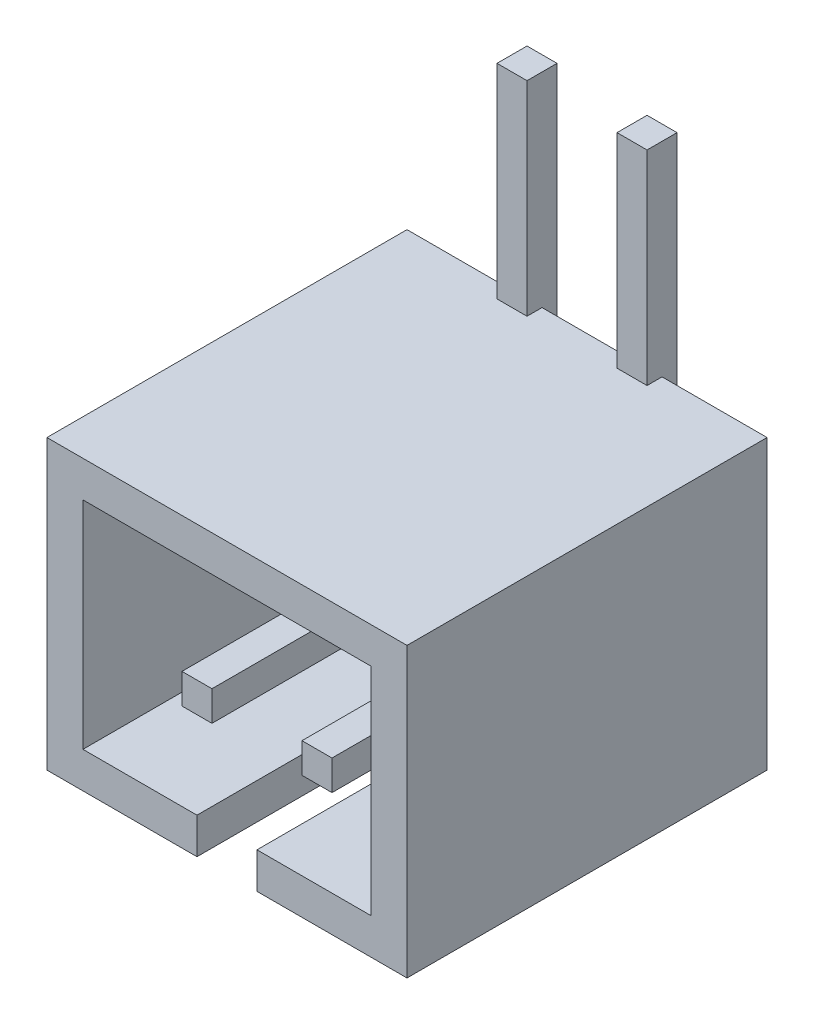
SolidWorks part; units mm, degrees
ref_plane "Front Plane" through (0, 0, 0) normal (0, 0, 1) x (1, 0, 0)
ref_plane "Top Plane" through (0, 0, 0) normal (0, 1, 0) x (1, 0, 0)
ref_plane "Right Plane" through (0, 0, 0) normal (1, 0, 0) x (0, 0, -1)
sketch "Sketch1" plane through (0, 0, 0) normal (0, 0, 1) x (1, 0, 0)
  line L1 (-3, 2.4) -> (3, 2.4)
  line L2 (-3, 2.4) -> (-3, -2.4)
  line L3 (-3, -2.4) -> (3, -2.4)
  line L4 (3, 2.4) -> (3, -2.4)
  line L5 (-3, 2.4) -> (3, -2.4) construction
  line L6 (-3, -2.4) -> (3, 2.4) construction
  point P0 (0, 0)
  dimension "D1" = 6
  dimension "D2" = 4.8
extrude "Boss-Extrude1" add sketch "Sketch1" along normal blind 2
sketch "Sketch2" plane through (0, 0, 2) normal (0, 0, 1) x (1, 0, 0)
  line L0 (-0.5, -2.4) -> (-0.5, -1.8)
  line L1 (-3, -2.4) -> (3, -2.4) construction
  line L2 (-0.5, -1.8) -> (-2.4, -1.8)
  line L3 (-2.4, -1.8) -> (-2.4, 1.8)
  line L4 (-2.4, 1.8) -> (2.4, 1.8)
  line L5 (0, 1.8) -> (0, 0) construction
  line L6 (-0.5, -2.4) -> (-3, -2.4)
  line L7 (-3, -2.4) -> (-3, 2.4)
  line L8 (-3, 2.4) -> (3, 2.4)
  line L9 (3, 2.4) -> (-3, 2.4) construction
  line L10 (3, -2.4) -> (3, 2.4)
  line L11 (0.5, -2.4) -> (3, -2.4)
  line L12 (0.5, -2.4) -> (0.5, -1.8)
  line L13 (0.5, -1.8) -> (2.4, -1.8)
  line L14 (2.4, -1.8) -> (2.4, 1.8)
  point P22 (0, 2.4)
  dimension "D1" = 2.5
  dimension "D2" = 0.6
  dimension "D3" = 0.6
  dimension "D4" = 0.6
extrude "Boss-Extrude2" add sketch "Sketch2" along normal offset from surface (4 mm away) 6 up to face at (0, 0, 0)
ref_plane "Plane1" through (-1, 0, 0) normal (-1, 0, 0) x (0, 0, 1)
sketch "Sketch3" plane through (-1, 0, 0) normal (-1, 0, 0) x (0, 0, 1)
  line L0 (0.25, 5.8) -> (0.25, -0.35)
  line L1 (0.25, -0.35) -> (5.5, -0.35)
  line L2 (5.5, -0.35) -> (5.5, -0.85)
  line L3 (5.5, -0.85) -> (-0.25, -0.85)
  line L4 (-0.25, -0.85) -> (-0.25, 5.8)
  line L5 (-0.25, 5.8) -> (0.25, 5.8)
  line L8 (6, -2.4) -> (0, -2.4) construction
  line L9 (0, 2.4) -> (0, -2.4) construction
  line L10 (6, 2.4) -> (0, 2.4) construction
  line L12 (0, 2.4) -> (0, 5.8) construction
  point P14 (5.5, -0.6)
  dimension "D1" = 0.5
  dimension "D2" = 0.5
  dimension "D3" = 8.2
  dimension "D4" = 3
  dimension "D5" = 5.5
extrude "Pin" add sketch "Sketch3" along normal mid plane 0.5
pattern_linear "LPattern1" count 2 spacing 2 along (1, 0, 0) of "Pin"
ref_plane "CenterPlane" through (0, 0, 0) normal (-1, 0, 0) x (0, 0, 1)
